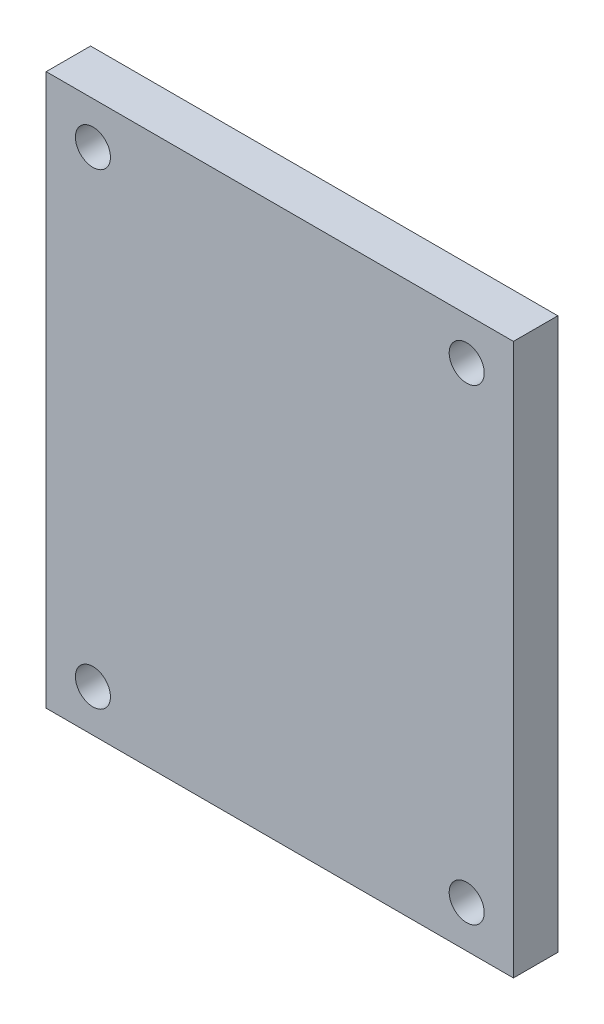
SolidWorks part; units mm, degrees
ref_plane "Front Plane" through (0, 0, 0) normal (0, 0, 1) x (1, 0, 0)
ref_plane "Top Plane" through (0, 0, 0) normal (0, 1, 0) x (1, 0, 0)
ref_plane "Right Plane" through (0, 0, 0) normal (1, 0, 0) x (0, 0, -1)
sketch "Sketch1" plane through (0, 0, 0) normal (0, 0, 1) x (1, 0, 0)
  line L0 (5.08, 55.372) -> (5.08, 4.572) construction
  line L1 (0, 0) -> (50.8, 0)
  line L2 (0, 0) -> (0, 59.944)
  line L3 (0, 59.944) -> (50.8, 59.944)
  line L4 (50.8, 0) -> (50.8, 59.944)
  line L5 (0, 29.972) -> (50.8, 29.972) construction
  line L6 (25.4, 59.944) -> (25.4, 29.972) construction
  circle A0 centre (5.08, 55.372) radius 1.905
  circle A1 centre (5.08, 4.572) radius 1.905
  circle A2 centre (45.72, 55.372) radius 1.905
  circle A3 centre (45.72, 4.572) radius 1.905
  dimension "D3" = 3.81
  dimension "D4" = 3.81
  dimension "D6" = 3.81
  dimension "D8" = 3.81
  dimension "D1" = 59.944
  dimension "D2" = 50.8
  dimension "D5" = 50.8
  dimension "D7" = 40.64
  dimension "D9" = 40.64
  dimension "D10" = 50.8
  dimension "D11" = 25.4
  dimension "D12" = 20.32
extrude "Boss-Extrude1" add sketch "Sketch1" along normal blind 4.826
equation "\"MDF\"= 0.19in"
equation "\"PVCID\" = 2.067in"
equation "\"PVCOD\" = 2.375in"
equation "\"GenDiameter\"= 60mm"
equation "\"GenCutDiameter\" = 1.8in"
equation "\"GenCutDistance\" = 1"
equation "\"TowerHeight\" = 6in"
equation "\"TowerFrontBase\" = 3in"
equation "\"FunnelHeight\" = 1in"
equation "\"FunnelAngle\" = 20"
equation "\"TowerSideBase\" = 3in"
equation "\"TowerPanelLength\" = 2in"
equation "\"TowerPanelLeeway\" = 0.5in"
equation "\"BaseLength\" = 9in"
equation "\"BaseWidth\" = 10in"
equation "\"WheelHoleLength\" = 3.25in"
equation "\"WheelHoleWidth\" = 26mm"
equation "\"WheelHoleFromBack\" = 1.5in"
equation "\"DropLength\" = 1in"
equation "\"DropWidth\" = 8.5in"
equation "\"BumperWidth\" = 1in"
equation "\"SmallHexDiameter\" = 0.185in"
equation "\"SmallHexHeight\" = 0.701in"
equation "\"ScrewSize\" = 0.106in"
equation "\"BigHexDiameter\" = 0.251in"
equation "\"BigHexHeight\" = 0.374in"
equation "\"PCBThickness\" = 0.066in"
equation "\"ConnectorHeight\" = 0.517in"
equation "\"BoardHeight\" = 0.583in"
equation "\"UnoStackHeight\" = 1.351in"
equation "\"UnoStackWidth\" = 3.053in"
equation "\"UnoStackLength\" = 3.152in"
equation "\"HBridgeWidth\" = 1.797in"
equation "\"HBridgeLength\" = 2.236in"
equation "\"DSWidth\" = 1.820in"
equation "\"DSLength\" = 1.833in"
equation "\"StepperWidth\" = 1.799in"
equation "\"StepperLength\" = 2.248in"
equation "\"ULNWidth\" = 1.304in"
equation "\"ULNLength\" = 1.545in"
equation "\"VSwitchHeight\" = 0.392in"
equation "\"VSwitchWidth\" = 0.637in"
equation "\"VSwitchLength\" = 1.097in"
equation "\"SkateWheelDiameter\" = 80mm"
equation "\"SkateWheelThickness\" = 24mm"
equation "\"BaseDistance\" = 3in"
equation "\"DummyVar\" = 2in"
equation "\"D1@Boss-Extrude1\"=\"MDF\""
